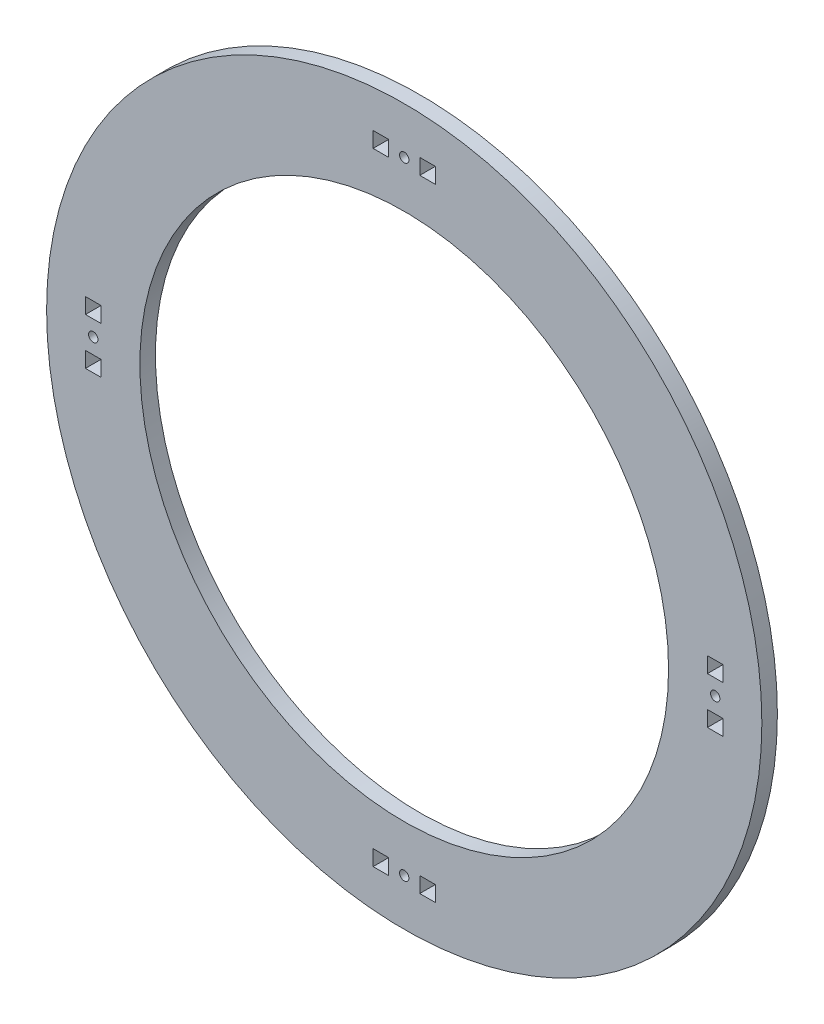
SolidWorks part; units mm, degrees
ref_plane "Front Plane" through (0, 0, 0) normal (0, 0, 1) x (1, 0, 0)
ref_plane "Top Plane" through (0, 0, 0) normal (0, 1, 0) x (1, 0, 0)
ref_plane "Right Plane" through (0, 0, 0) normal (1, 0, 0) x (0, 0, -1)
sketch "Esquisse1" plane through (0, 0, 0) normal (0, 0, 1) x (1, 0, 0)
  line L0 (0, 129.3346) -> (0, -149.5024) construction
  circle A0 centre (0, 0) radius 115
  circle A1 centre (0, 0) radius 85
  circle A2 centre (0, 0) radius 100 construction
  point P8 (0, 0)
  line B0 (-100, -5) -> (-100, 5) construction
  line B1 (-102.5, -5) -> (-102.5, -10)
  line B2 (-102.5, -5) -> (-97.5, -5)
  line B3 (-97.5, -5) -> (-97.5, -10)
  line B4 (-102.5, -10) -> (-97.5, -10)
  line B5 (-102.5, 5) -> (-102.5, 10)
  line B6 (-102.5, 5) -> (-97.5, 5)
  line B7 (-97.5, 5) -> (-97.5, 10)
  line B8 (-102.5, 10) -> (-97.5, 10)
  line B9 (-100, 0) -> (-106.2802, 0) construction
  circle B10 centre (-100, 0) radius 1.5
  line B11 (-102.5, 10) -> (-97.5, 5) construction
  line B12 (-102.5, -5) -> (-97.5, -10) construction
  line B13 (-5, 102.5) -> (-10, 102.5)
  line B14 (-5, 102.5) -> (-5, 97.5)
  line B15 (-5, 97.5) -> (-10, 97.5)
  line B16 (-10, 102.5) -> (-10, 97.5)
  line B17 (5, 102.5) -> (10, 102.5)
  line B18 (5, 102.5) -> (5, 97.5)
  line B19 (5, 97.5) -> (10, 97.5)
  line B20 (10, 102.5) -> (10, 97.5)
  line B21 (0, 100) -> (0, 106.2802) construction
  circle B22 centre (0, 100) radius 1.5
  line B23 (102.5, 5) -> (102.5, 10)
  line B24 (102.5, 5) -> (97.5, 5)
  line B25 (97.5, 5) -> (97.5, 10)
  line B26 (102.5, 10) -> (97.5, 10)
  line B27 (102.5, -5) -> (102.5, -10)
  line B28 (102.5, -5) -> (97.5, -5)
  line B29 (97.5, -5) -> (97.5, -10)
  line B30 (102.5, -10) -> (97.5, -10)
  circle B31 centre (100, 0) radius 1.5
  line B32 (5, -102.5) -> (10, -102.5)
  line B33 (5, -102.5) -> (5, -97.5)
  line B34 (5, -97.5) -> (10, -97.5)
  line B35 (10, -102.5) -> (10, -97.5)
  line B36 (-5, -102.5) -> (-10, -102.5)
  line B37 (-5, -102.5) -> (-5, -97.5)
  line B38 (-5, -97.5) -> (-10, -97.5)
  line B39 (-10, -102.5) -> (-10, -97.5)
  circle B40 centre (0, -100) radius 1.5
sketch_block_instance "Trou M3 plots 5mm-53"
sketch_block "Trou M3 plots 5mm" parameters "D2"=3, "D1"=5, "D3"=5, "D4"=8
sketch_block_instance "Trou M3 plots 5mm-55"
sketch_block_instance "Trou M3 plots 5mm-56"
sketch_block_instance "Trou M3 plots 5mm-57" parameters "D1"=54.2135, "D3"=2.7166, "D4"=100.0009, "D2"=95.9432
extrude "Boss.-Extru.1" add sketch "Esquisse1" along normal blind 5
